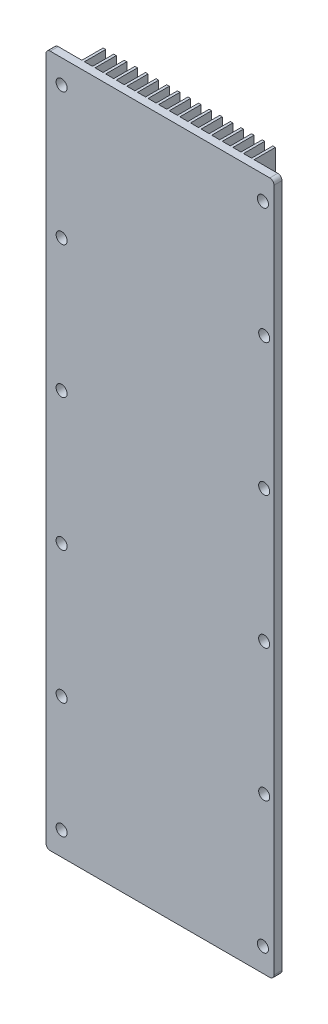
SolidWorks part; units mm, degrees
material "6063-T5"
ref_plane "X-Y Datum" through (0, 0, 0) normal (0, 0, 1) x (1, 0, 0)
ref_plane "X-Z Datum" through (0, 0, 0) normal (0, 1, 0) x (1, 0, 0)
ref_plane "Y-Z Datum" through (0, 0, 0) normal (1, 0, 0) x (0, 0, -1)
sketch "Sketch1" plane through (0, 0, 0) normal (0, 1, 0) x (1, 0, 0)
  line L0 (0, 9.525) -> (4.0132, 9.525) construction
  line L1 (0, 0) -> (136.525, 0)
  line L2 (0, 0) -> (0, 9.525)
  line L3 (0, 9.525) -> (4.0132, 9.525)
  line L4 (136.525, 0) -> (136.525, 9.525)
  line L5 (4.7752, 9.525) -> (4.7752, 34.925) construction
  line L6 (4.0132, 34.925) -> (4.0132, 9.525)
  line L7 (5.5372, 34.925) -> (5.5372, 9.525)
  line L8 (11.8872, 34.925) -> (11.8872, 9.525)
  line L9 (10.3632, 34.925) -> (10.3632, 9.525)
  line L10 (18.2372, 34.925) -> (18.2372, 9.525)
  line L11 (16.7132, 34.925) -> (16.7132, 9.525)
  line L12 (24.5872, 34.925) -> (24.5872, 9.525)
  line L13 (23.0632, 34.925) -> (23.0632, 9.525)
  line L14 (30.9372, 34.925) -> (30.9372, 9.525)
  line L15 (29.4132, 34.925) -> (29.4132, 9.525)
  line L16 (37.2872, 34.925) -> (37.2872, 9.525)
  line L17 (35.7632, 34.925) -> (35.7632, 9.525)
  line L18 (43.6372, 34.925) -> (43.6372, 9.525)
  line L19 (42.1132, 34.925) -> (42.1132, 9.525)
  line L20 (49.9872, 34.925) -> (49.9872, 9.525)
  line L21 (48.4632, 34.925) -> (48.4632, 9.525)
  line L22 (56.3372, 34.925) -> (56.3372, 9.525)
  line L23 (54.8132, 34.925) -> (54.8132, 9.525)
  line L24 (62.6872, 34.925) -> (62.6872, 9.525)
  line L25 (61.1632, 34.925) -> (61.1632, 9.525)
  line L26 (69.0372, 34.925) -> (69.0372, 9.525)
  line L27 (67.5132, 34.925) -> (67.5132, 9.525)
  line L28 (75.3872, 34.925) -> (75.3872, 9.525)
  line L29 (73.8632, 34.925) -> (73.8632, 9.525)
  line L30 (81.7372, 34.925) -> (81.7372, 9.525)
  line L31 (80.2132, 34.925) -> (80.2132, 9.525)
  line L32 (88.0872, 34.925) -> (88.0872, 9.525)
  line L33 (86.5632, 34.925) -> (86.5632, 9.525)
  line L34 (94.4372, 34.925) -> (94.4372, 9.525)
  line L35 (92.9132, 34.925) -> (92.9132, 9.525)
  line L36 (100.7872, 34.925) -> (100.7872, 9.525)
  line L37 (99.2632, 34.925) -> (99.2632, 9.525)
  line L38 (107.1372, 34.925) -> (107.1372, 9.525)
  line L39 (105.6132, 34.925) -> (105.6132, 9.525)
  line L40 (113.4872, 34.925) -> (113.4872, 9.525)
  line L41 (111.9632, 34.925) -> (111.9632, 9.525)
  line L42 (119.8372, 34.925) -> (119.8372, 9.525)
  line L43 (118.3132, 34.925) -> (118.3132, 9.525)
  line L44 (126.1872, 34.925) -> (126.1872, 9.525)
  line L45 (124.6632, 34.925) -> (124.6632, 9.525)
  line L46 (132.5372, 34.925) -> (132.5372, 9.525)
  line L47 (131.0132, 34.925) -> (131.0132, 9.525)
  line L48 (5.5372, 9.525) -> (10.3632, 9.525)
  line L49 (11.8872, 9.525) -> (16.7132, 9.525)
  line L50 (24.5872, 9.525) -> (29.4132, 9.525)
  line L51 (30.9372, 9.525) -> (35.7632, 9.525)
  line L52 (18.2372, 9.525) -> (23.0632, 9.525)
  line L53 (37.2872, 9.525) -> (42.1132, 9.525)
  line L54 (43.6372, 9.525) -> (48.4632, 9.525)
  line L55 (49.9872, 9.525) -> (54.8132, 9.525)
  line L56 (56.3372, 9.525) -> (61.1632, 9.525)
  line L57 (62.6872, 9.525) -> (67.5132, 9.525)
  line L58 (69.0372, 9.525) -> (73.8632, 9.525)
  line L59 (75.3872, 9.525) -> (80.2132, 9.525)
  line L60 (81.7372, 9.525) -> (86.5632, 9.525)
  line L61 (88.0872, 9.525) -> (92.9132, 9.525)
  line L62 (94.4372, 9.525) -> (99.2632, 9.525)
  line L63 (100.7872, 9.525) -> (105.6132, 9.525)
  line L64 (107.1372, 9.525) -> (111.9632, 9.525)
  line L65 (113.4872, 9.525) -> (118.3132, 9.525)
  line L66 (119.8372, 9.525) -> (124.6632, 9.525)
  line L67 (126.1872, 9.525) -> (131.0132, 9.525)
  line L68 (132.5372, 9.525) -> (136.525, 9.525)
  arc A0 (5.5372, 34.925) -> (4.0132, 34.925) centre (4.7752, 34.925) ccw
  arc A1 (11.8872, 34.925) -> (10.3632, 34.925) centre (11.1252, 34.925) ccw
  arc A2 (18.2372, 34.925) -> (16.7132, 34.925) centre (17.4752, 34.925) ccw
  arc A3 (24.5872, 34.925) -> (23.0632, 34.925) centre (23.8252, 34.925) ccw
  arc A4 (30.9372, 34.925) -> (29.4132, 34.925) centre (30.1752, 34.925) ccw
  arc A5 (37.2872, 34.925) -> (35.7632, 34.925) centre (36.5252, 34.925) ccw
  arc A6 (43.6372, 34.925) -> (42.1132, 34.925) centre (42.8752, 34.925) ccw
  arc A7 (49.9872, 34.925) -> (48.4632, 34.925) centre (49.2252, 34.925) ccw
  arc A8 (56.3372, 34.925) -> (54.8132, 34.925) centre (55.5752, 34.925) ccw
  arc A9 (62.6872, 34.925) -> (61.1632, 34.925) centre (61.9252, 34.925) ccw
  arc A10 (69.0372, 34.925) -> (67.5132, 34.925) centre (68.2752, 34.925) ccw
  arc A11 (75.3872, 34.925) -> (73.8632, 34.925) centre (74.6252, 34.925) ccw
  arc A12 (81.7372, 34.925) -> (80.2132, 34.925) centre (80.9752, 34.925) ccw
  arc A13 (88.0872, 34.925) -> (86.5632, 34.925) centre (87.3252, 34.925) ccw
  arc A14 (94.4372, 34.925) -> (92.9132, 34.925) centre (93.6752, 34.925) ccw
  arc A15 (100.7872, 34.925) -> (99.2632, 34.925) centre (100.0252, 34.925) ccw
  arc A16 (107.1372, 34.925) -> (105.6132, 34.925) centre (106.3752, 34.925) ccw
  arc A17 (113.4872, 34.925) -> (111.9632, 34.925) centre (112.7252, 34.925) ccw
  arc A18 (119.8372, 34.925) -> (118.3132, 34.925) centre (119.0752, 34.925) ccw
  arc A19 (126.1872, 34.925) -> (124.6632, 34.925) centre (125.4252, 34.925) ccw
  arc A20 (132.5372, 34.925) -> (131.0132, 34.925) centre (131.7752, 34.925) ccw
  dimension "D1" = 21
extrude "Boss-Extrude1" add sketch "Sketch1" along normal blind 431.8
sketch "Sketch2" plane through (0, 431.8, 0) normal (0, 1, 0) x (1, 0, 0)
  line L0 (136.525, 0) -> (136.525, 9.525) construction
  line L1 (0, 0) -> (136.525, 0)
  line L2 (0, 0) -> (0, 4.7625)
  line L3 (0, 4.7625) -> (136.525, 4.7625)
  line L4 (136.525, 0) -> (136.525, 4.7625)
extrude "Cut-Extrude1" cut sketch "Sketch2" against normal through all
sketch "Sketch3" plane through (0, 0, 0) normal (0, -1, 0) x (1, 0, 0)
  line L1 (3.1502, -35.687) -> (135.4162, -35.687)
  line L2 (3.1502, -35.687) -> (3.1502, -22.225)
  line L3 (3.1502, -22.225) -> (135.4162, -22.225)
  line L4 (135.4162, -35.687) -> (135.4162, -22.225)
extrude "Cut-Extrude2" cut sketch "Sketch3" against normal through all
sketch "Sketch4" plane through (0, 431.8, 0) normal (0, 1, 0) x (1, 0, 0)
  line L0 (4.0132, 9.525) -> (0, 9.525) construction
  line L1 (2.0066, 9.525) -> (13.6072, 9.525)
  line L2 (2.0066, 9.525) -> (2.0066, 23.6287)
  line L3 (2.0066, 23.6287) -> (13.6072, 23.6287)
  line L4 (13.6072, 9.525) -> (13.6072, 23.6287)
  line L5 (136.525, 9.525) -> (132.5372, 9.525) construction
  line L6 (134.5311, 9.525) -> (122.2502, 9.525)
  line L7 (134.5311, 9.525) -> (134.5311, 24.4435)
  line L8 (134.5311, 24.4435) -> (122.2502, 24.4435)
  line L9 (122.2502, 9.525) -> (122.2502, 24.4435)
  line L10 (124.6632, 9.525) -> (119.8372, 9.525) construction
extrude "Cut-Extrude3" cut sketch "Sketch4" against normal through all
sketch "Sketch5" plane through (0, 0, -9.525) normal (0, 0, -1) x (-1, 0, 0)
  line L1 (-136.525, 431.8) -> (0, 431.8)
  line L2 (-136.525, 431.8) -> (-136.525, 17.156) construction
  line L3 (-136.525, 17.156) -> (0, 17.156)
  line L4 (0, 431.8) -> (0, 17.156)
  line L5 (-136.525, 17.156) -> (0, 17.156)
  line L6 (-136.525, 17.156) -> (-136.525, 0)
  line L7 (-136.525, 0) -> (0, 0)
  line L8 (0, 17.156) -> (0, 0)
  line M5 (-119.8372, 0) -> (-119.8372, 431.8)
  line M7 (-136.525, 431.8) -> (-136.525, 0)
  line M8 (-136.525, 0) -> (-119.8372, 0)
extrude "Cut-Extrude4" cut sketch "Sketch5" against normal through all both and the other way through all contours L3 M7 M8 M5 | L8 L3 L7 M5
sketch "Sketch10" plane through (0, 0, -4.7625) normal (0, 0, 1) x (1, 0, 0)
  line L0 (26.855, 99.822) -> (26.855, 101.484) construction
  line L1 (9.3248, 100.653) -> (9.3248, 179.901) construction
  line L2 (9.3248, 179.901) -> (9.3248, 259.149) construction
  line L3 (9.3248, 259.149) -> (9.3248, 338.397) construction
  line L4 (64.8978, 17.156) -> (64.8978, 431.8) construction
  line L5 (26.855, 100.653) -> (9.3248, 100.653) construction
  line L6 (64.8978, 224.478) -> (-24.6242, 224.478) construction
  line L7 (113.1007, 349.134) -> (113.1007, 347.472) construction
  line L8 (26.855, 179.07) -> (26.855, 180.732) construction
  line L9 (26.855, 179.901) -> (9.3248, 179.901) construction
  line L10 (26.855, 258.318) -> (26.855, 259.98) construction
  line L11 (26.855, 259.149) -> (9.3248, 259.149) construction
  line L12 (26.855, 337.566) -> (26.855, 339.228) construction
  line L13 (26.855, 338.397) -> (9.3248, 338.397) construction
  line L14 (113.1007, 109.728) -> (113.1007, 111.39) construction
  line L15 (113.1007, 110.559) -> (130.6309, 110.559) construction
  line L16 (113.1007, 188.976) -> (113.1007, 190.638) construction
  line L17 (113.1007, 189.807) -> (130.6309, 189.807) construction
  line L18 (113.1007, 268.224) -> (113.1007, 269.886) construction
  line L19 (113.1007, 269.055) -> (130.6309, 269.055) construction
  line L20 (113.1007, 348.303) -> (130.6309, 348.303) construction
  line L21 (64.8978, 224.478) -> (139.9557, 224.478) construction
  line L22 (9.3248, 31.311) -> (129.903, 31.311) construction
  line L23 (9.3248, 31.311) -> (9.3248, 17.156) construction
  line L24 (9.3248, 17.156) -> (0, 17.156) construction
  point P3 (9.3248, 100.653)
  point P12 (9.3248, 31.311)
  point P13 (130.6309, 348.303)
  point P24 (130.6309, 189.807)
  point P26 (130.6309, 269.055)
  point P28 (130.6309, 110.559)
  point P57 (129.903, 417.645)
  point P58 (129.903, 31.311)
  point P59 (9.3248, 417.645)
  dimension "D1" = 17.5302
fillet "Fillet1" radius 2.54 4 edges at (136.525, 17.156, -7.1437) (136.525, 431.8, -7.1437) (0, 431.8, -7.1437) (0, 17.156, -7.1437)
hole_wizard "M6 Clearance Hole2" positions "Sketch13" profile "Sketch14" hole size "M6" standard "ANSI Metric" end condition through all
sketch "Sketch13" plane through (0, 0, -4.7625) normal (0, 0, 1) x (1, 0, 0)
  point P10 (9.3248, 31.311)
  point P13 (129.903, 31.311)
  point P16 (130.6309, 110.559)
  point P19 (9.3248, 100.653)
  point P22 (9.3248, 179.901)
  point P25 (130.6309, 189.807)
  point P28 (9.3248, 259.149)
  point P31 (130.6309, 269.055)
  point P34 (130.6309, 348.303)
  point P37 (9.3248, 338.397)
  point P40 (9.3248, 417.645)
  point P43 (129.903, 417.645)
sketch "Sketch14" plane through (9.3248, 31.311, -4.7625) normal (1, 0, 0) x (0, -1, 0)
  line L0 (0, 0) -> (0, 17.4625)
  line L1 (0, 17.4625) -> (3.3, 17.4625)
  line L2 (3.3, 17.4625) -> (3.3, 0)
  line L5 (3.3, 0) -> (0, 0)
  line L11 (0, -6.35) -> (0, 107.95) construction
  dimension "Thru Hole Dia." = 6.6
  dimension "Thru Hole Depth" = 17.4625
